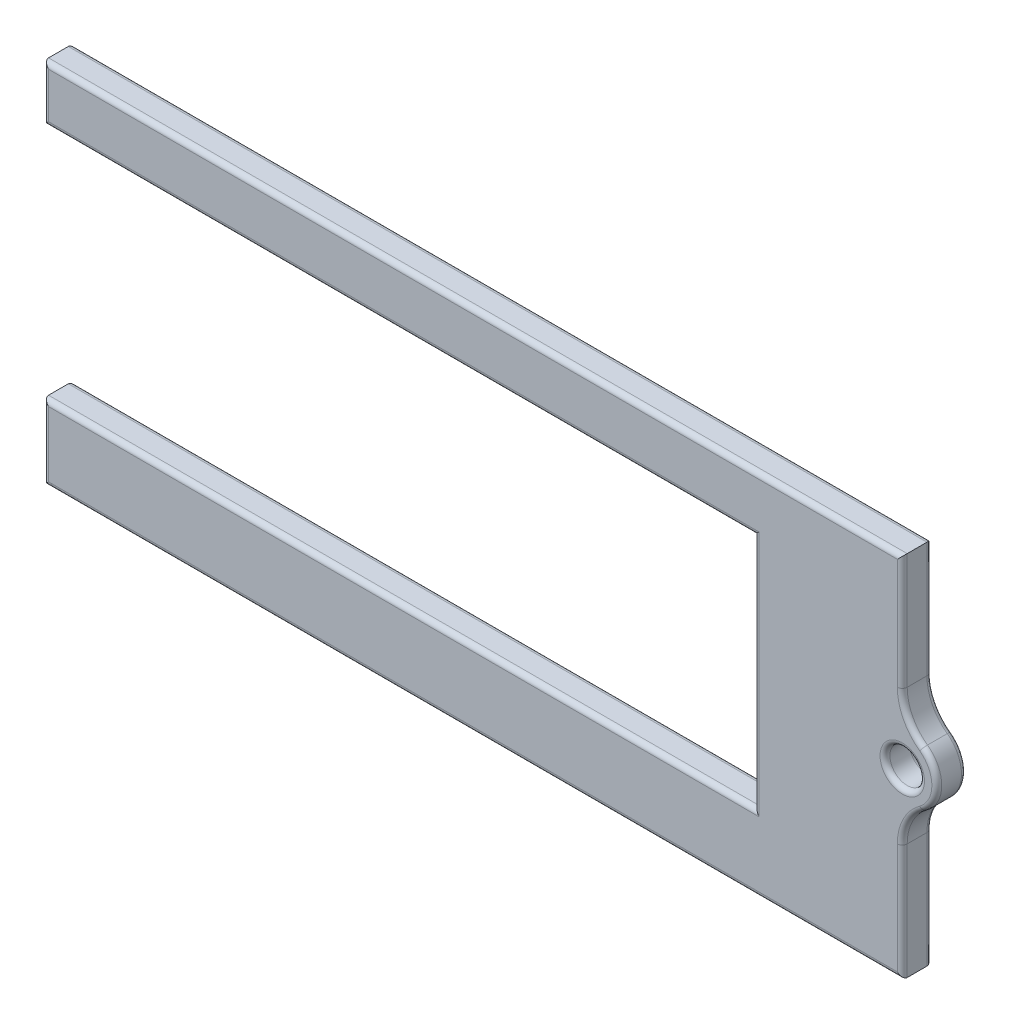
SolidWorks part; units mm, degrees
ref_plane "Front Plane" through (0, 0, 0) normal (0, 0, 1) x (1, 0, 0)
ref_plane "Top Plane" through (0, 0, 0) normal (0, 1, 0) x (1, 0, 0)
ref_plane "Right Plane" through (0, 0, 0) normal (1, 0, 0) x (0, 0, -1)
sketch "Sketch1" plane through (0, 0, 0) normal (0, 0, 1) x (1, 0, 0)
  line L0 (-266.5, 139.6) -> (-179.5, 139.6)
  line L1 (-266.5, 102.4) -> (-179.5, 102.4)
  line L18 (-179.5, 102.4) -> (-179.5, 114.1261)
  line L19 (-179.5, 127.8739) -> (-179.5, 139.6)
  line L20 (-179.5, 140) -> (-266.5, 140) construction
  line L21 (-266.5, 139.6) -> (-266.5, 134)
  line L22 (-266.5, 134) -> (-194.5, 134)
  line L23 (-194.5, 134) -> (-194.5, 110)
  line L24 (-194.5, 110) -> (-266.5, 110)
  line L25 (-266.5, 110) -> (-266.5, 102.4)
  line L26 (-266.5, 102) -> (-179.5, 102) construction
  circle A0 centre (-179.5, 121) radius 1.75
  arc A1 (-177.4412, 123.8304) -> (-179.5, 127.8739) centre (-174.5, 127.8739) cw
  arc A2 (-177.4412, 118.1696) -> (-177.4412, 123.8304) centre (-179.5, 121) ccw
  arc A3 (-179.5, 114.1261) -> (-177.4412, 118.1696) centre (-174.5, 114.1261) cw
  dimension "D4" = 3.5
  dimension "D5" = 5
  dimension "D1" = 6
  dimension "D2" = 8
  dimension "D3" = 15
  dimension "D6" = 0.4
  dimension "D7" = 0.4
extrude "Boss-Extrude1" add sketch "Sketch1" along normal blind 3
fillet "Fillet1" radius 0.5 26 edges at (-177.75, 121, 0) (-178.9557, 125.6052, 0) (-179.5, 133.7369, 0) (-223, 139.6, 0) (-266.5, 136.8, 0) (-230.5, 134, 0) (-194.5, 122, 0) (-230.5, 110, 0) (-266.5, 106.2, 0) (-223, 102.4, 0) (-179.5, 108.2631, 0) (-178.9557, 116.3948, 0) (-176, 121, 0) (-177.75, 121, 3) (-178.9557, 116.3948, 3) (-179.5, 108.2631, 3) (-223, 102.4, 3) (-266.5, 106.2, 3) (-230.5, 110, 3) (-194.5, 122, 3) (-230.5, 134, 3) (-266.5, 136.8, 3) (-223, 139.6, 3) (-179.5, 133.7369, 3) (-178.9557, 125.6052, 3) (-176, 121, 3)
